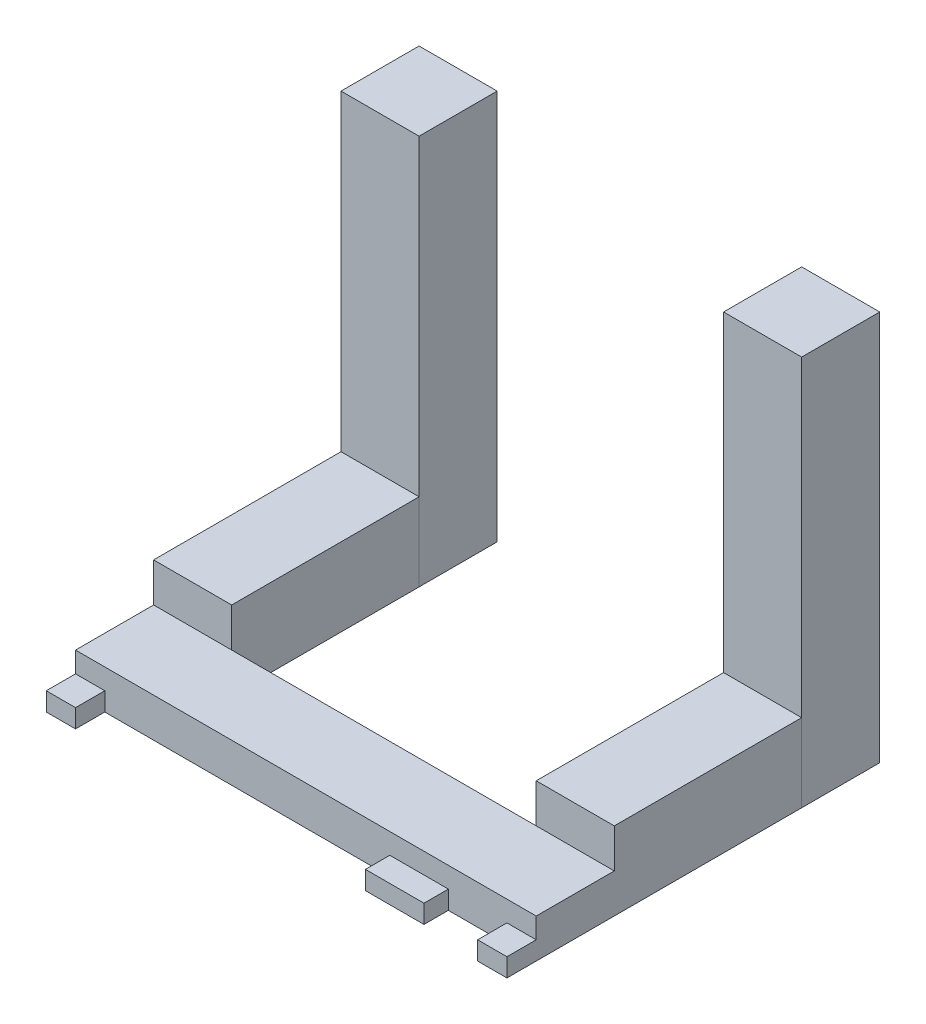
SolidWorks part; units mm, degrees
ref_plane "Front Plane" through (0, 0, 0) normal (0, 0, 1) x (1, 0, 0)
ref_plane "Top Plane" through (0, 0, 0) normal (0, 1, 0) x (1, 0, 0)
ref_plane "Right Plane" through (0, 0, 0) normal (1, 0, 0) x (0, 0, -1)
sketch "Sketch1" plane through (0, 0, 0) normal (0, 1, 0) x (1, 0, 0)
  line L0 (0, 0) -> (-74.93, 0)
  line L2 (-74.93, 0) -> (-62.23, 0)
  line L3 (-74.93, 0) -> (-74.93, 12.7)
  line L4 (-74.93, 12.7) -> (-62.23, 12.7)
  line L5 (-62.23, 0) -> (-62.23, 12.7)
  line L6 (0, 0) -> (-12.7, 0)
  line L7 (0, 0) -> (0, 12.7)
  line L8 (0, 12.7) -> (-12.7, 12.7)
  line L9 (-12.7, 0) -> (-12.7, 12.7)
  dimension "D1" = 74.93
  dimension "D2" = 12.7
  dimension "D3" = 12.7
  dimension "D4" = 12.7
  dimension "D5" = 12.7
extrude "Boss-Extrude1" add sketch "Sketch1" along normal blind 63.5 contours L0 L5 L4 L3 | L9 L0 L7 L8
sketch "Sketch2" plane through (0, 0, 0) normal (0, 0, 1) x (1, 0, 0)
  line L0 (0, 63.5) -> (0, 0) construction
  line L1 (-74.93, 0) -> (0, 0)
  line L2 (-74.93, 0) -> (-74.93, 12.7)
  line L3 (-74.93, 12.7) -> (0, 12.7)
  line L4 (0, 0) -> (0, 12.7)
  dimension "D1" = 12.7
ref_plane "Plane1" through (-37.465, 0, 0) normal (1, 0, 0) x (0, 0, -1)
sketch "Sketch5" plane through (0, 0, 0) normal (0, 0, 1) x (1, 0, 0)
  line L0 (-74.93, 63.5) -> (-74.93, 0) construction
  line L1 (-62.23, 12.7) -> (-74.93, 12.7)
  line L2 (-62.23, 12.7) -> (-62.23, 0)
  line L3 (-62.23, 0) -> (-74.93, 0)
  line L4 (-74.93, 12.7) -> (-74.93, 0)
  line L5 (-12.7, 12.7) -> (0, 12.7)
  line L6 (-12.7, 12.7) -> (-12.7, 0)
  line L7 (-12.7, 0) -> (0, 0)
  line L8 (0, 12.7) -> (0, 0)
  line L9 (-74.93, 12.7) -> (0, 12.7) construction
  point P12 (0, 0)
  point P13 (-74.93, 0.038)
  point P16 (0, 0)
  point P17 (0, 0)
  point P19 (0, 0)
  point P20 (-62.313, 12.7)
  point P23 (-62.23, 0)
  point P25 (0, 0)
  point P26 (-12.666, 12.7)
extrude "Boss-Extrude5" add sketch "Sketch5" along normal blind 30.48
sketch "Sketch6" plane through (0, 0, 30.48) normal (0, 0, 1) x (1, 0, 0)
  line L0 (-74.93, 6.35) -> (0, 6.35)
  line L1 (-74.93, 12.7) -> (0, 12.7)
  line L2 (-74.93, 12.7) -> (-74.93, 0)
  line L3 (-74.93, 0) -> (0, 0)
  line L4 (0, 12.7) -> (0, 0)
  line M1 (-62.23, 0) -> (-62.23, 12.7)
  line M3 (-74.93, 12.7) -> (-74.93, 0)
  line M4 (-74.93, 0) -> (-62.23, 0)
extrude "Boss-Extrude6" add sketch "Sketch6" along normal blind 12.7 contours L4 L0 L3 M1 | L0 M3 M4 M1
sketch "Sketch4" plane through (0, 0, 43.18) normal (0, 0, 1) x (1, 0, 0)
  line L0 (-62.23, 0) -> (-74.93, 0) construction
  line L1 (-23.8125, 0) -> (-14.2875, 0)
  line L2 (-23.8125, 0) -> (-23.8125, 3)
  line L3 (-23.8125, 3) -> (-14.2875, 3)
  line L4 (-14.2875, 0) -> (-14.2875, 3)
  dimension "D1" = 23.8125
  dimension "D2" = 9.525
  dimension "D3" = 3
extrude "Boss-Extrude4" add sketch "Sketch4" along normal blind 3.9688
sketch "Sketch3" plane through (0, 0, 43.18) normal (0, 0, 1) x (1, 0, 0)
  line L1 (0, 0) -> (-4.7625, 0)
  line L2 (0, 0) -> (0, 3)
  line L3 (0, 3) -> (-4.7625, 3)
  line L4 (-4.7625, 0) -> (-4.7625, 3)
  point P5 (0, 0)
  point P6 (0, 0)
  dimension "D1" = 3
  dimension "D2" = 4.7625
extrude "Boss-Extrude7" add sketch "Sketch3" along normal blind 4.7625
mirror "Mirror2" about plane through (-37.465, 0, 0) normal (1, 0, 0) of "Boss-Extrude7"
